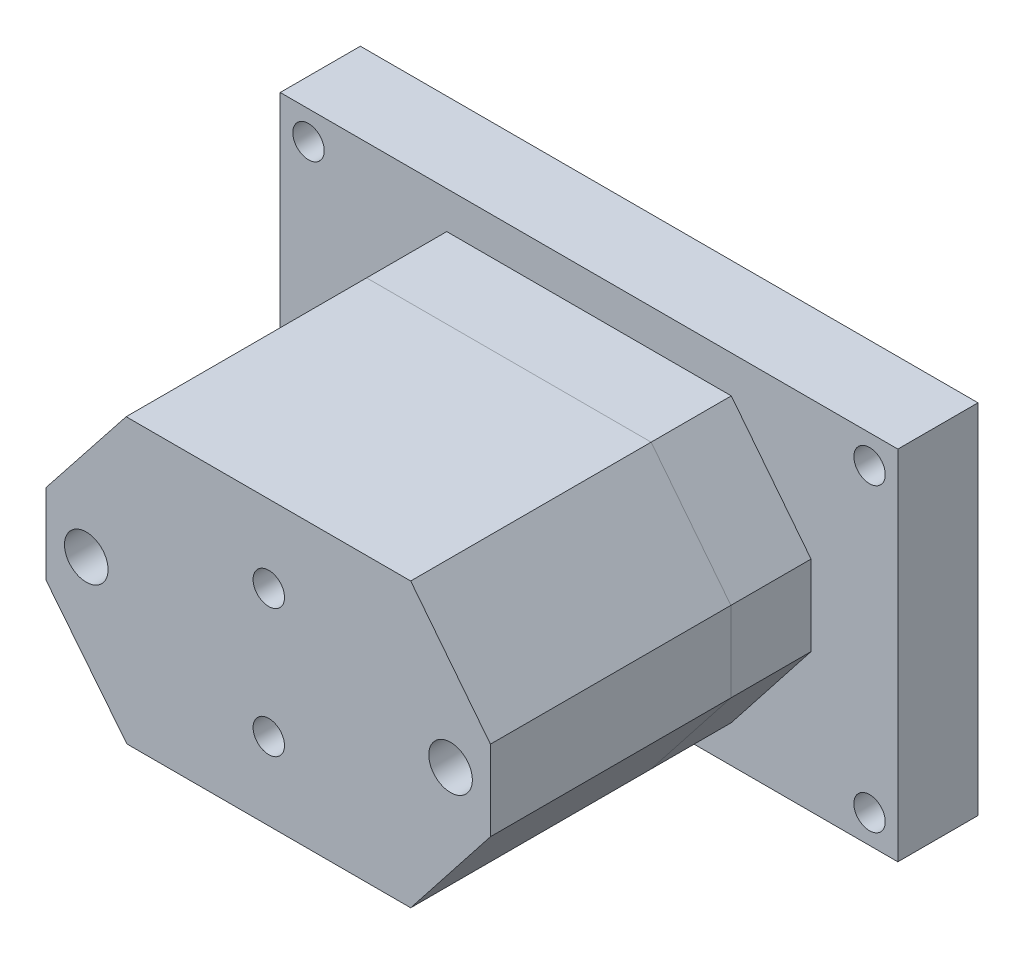
SolidWorks part; units mm, degrees
ref_plane "Alzado" through (0, 0, 0) normal (0, 0, 1) x (1, 0, 0)
ref_plane "Planta" through (0, 0, 0) normal (0, 1, 0) x (1, 0, 0)
ref_plane "Vista lateral" through (0, 0, 0) normal (1, 0, 0) x (0, 0, -1)
other "Gráfico1"
other "Gráfico (Cerrada) -1"
sketch "Croquis1" plane through (0, 0, 0) normal (0, 0, 1) x (1, 0, 0)
  line L0 (4.779, 6.731) -> (11.1125, 6.731)
  line L1 (-19.25, 19.25) -> (19.25, 19.25)
  line L2 (-19.25, 19.25) -> (-19.25, -19.25)
  line L3 (-19.25, -19.25) -> (19.25, -19.25)
  line L4 (19.25, 19.25) -> (19.25, -19.25)
  line L5 (-11.1125, 6.731) -> (-4.779, 6.731)
  line L6 (-11.1125, 6.731) -> (-11.1125, -6.731)
  line L7 (-11.1125, -6.731) -> (-4.779, -6.731)
  line L8 (11.1125, 6.731) -> (11.1125, -6.731)
  line L9 (4.779, -6.731) -> (11.1125, -6.731)
  line L10 (-8.6716, 0) -> (7.9627, 0) construction
  arc A0 (-4.779, -6.731) -> (4.779, -6.731) centre (0, 0) ccw
  arc A1 (4.779, 6.731) -> (-4.779, 6.731) centre (0, 0) ccw
  circle A2 centre (-14, 14) radius 1.632
  circle A4 centre (14, 14) radius 1.632
  circle A5 centre (14, -14) radius 1.632
  circle A6 centre (-14, -14) radius 1.632
  dimension "D1" = 3.2639
extrude "Saliente-Extruir1" add sketch "Croquis1" along normal blind 3.175
sketch "Croquis3" plane through (0, -19.25, 0) normal (0, -1, 0) x (1, 0, 0)
  line L1 (-22.5425, 18.415) -> (22.5425, 18.415)
  line L2 (-22.5425, 18.415) -> (-22.5425, 0)
  line L3 (-22.5425, 0) -> (22.5425, 0)
  line L4 (22.5425, 18.415) -> (22.5425, 0)
extrude "Saliente-Extruir3" add sketch "Croquis3" along normal blind 3.175
sketch "Croquis4" plane through (-19.25, 0, 0) normal (-1, 0, 0) x (0, 0, 1)
  line L1 (0, 19.25) -> (18.415, 19.25)
  line L2 (0, 19.25) -> (0, -19.25)
  line L3 (0, -19.25) -> (18.415, -19.25)
  line L4 (18.415, 19.25) -> (18.415, -19.25)
extrude "Saliente-Extruir4" add sketch "Croquis4" along normal blind 3.175
sketch "Croquis5" plane through (19.25, 0, 0) normal (1, 0, 0) x (0, 0, -1)
  line L0 (-12.6177, -7.6849) -> (-18.415, -7.6849)
  line L1 (0, 19.25) -> (-18.415, 19.25)
  line L2 (0, 19.25) -> (0, -19.25)
  line L3 (0, -19.25) -> (-18.415, -19.25)
  line L4 (-18.415, 19.25) -> (-18.415, -7.6849)
  line L5 (-12.3487, -12.3047) -> (-18.415, -12.3047)
  line L6 (-18.415, -12.3047) -> (-18.415, -19.25)
  arc A0 (-12.6177, -7.6849) -> (-12.3487, -12.3047) centre (-12.8905, -10.0186) cw
extrude "Saliente-Extruir5" add sketch "Croquis5" along normal blind 3.175
sketch "Croquis6" plane through (0, 19.25, 0) normal (0, 1, 0) x (1, 0, 0)
  line L1 (-22.5425, 0) -> (22.5425, 0)
  line L2 (-22.5425, 0) -> (-22.5425, -18.415)
  line L3 (-22.5425, -18.415) -> (22.5425, -18.415)
  line L4 (22.5425, 0) -> (22.5425, -18.415)
extrude "Saliente-Extruir6" add sketch "Croquis6" along normal blind 3.175
sketch "Croquis7" plane through (0, 0, 0) normal (0, 0, 1) x (1, 0, 0)
  line L0 (-22.425, -19.25) -> (-22.425, 19.25) construction
  line L1 (-35.2425, 6.35) -> (-22.425, 6.35)
  line L2 (-35.2425, 6.35) -> (-35.2425, -6.35)
  line L3 (-35.2425, -6.35) -> (-22.425, -6.35)
  line L4 (-22.425, 6.35) -> (-22.425, -6.35)
  line L6 (0, 0) -> (0, -15.2959) construction
  line L7 (22.425, 6.35) -> (22.425, -6.35)
  line L8 (35.2425, -6.35) -> (22.425, -6.35)
  line L9 (35.2425, 6.35) -> (35.2425, -6.35)
  line L10 (35.2425, 6.35) -> (22.425, 6.35)
  line L11 (-28.8338, 6.35) -> (-28.8338, -6.35) construction
  circle A1 centre (-28.8338, 0) radius 2.4892
  circle A2 centre (28.8338, 0) radius 2.4892
  dimension "D1" = 4.9784
  dimension "D2" = 12.7
extrude "Saliente-Extruir7" add sketch "Croquis7" along normal up to vertex (18.415 mm away)
sketch "Croquis10" plane through (0, 0, 0) normal (1, 0, 0) x (0, 0, -1)
  line L0 (0, -22.425) -> (-18.415, -22.425) construction
  line L1 (2.54, 22.425) -> (40.64, 22.425)
  line L2 (2.54, 22.425) -> (2.54, -22.425)
  line L3 (2.54, -22.425) -> (40.64, -22.425)
  line L4 (40.64, 22.425) -> (40.64, -22.425)
  line L5 (-18.415, 22.425) -> (0, 22.425) construction
  line L6 (0, -19.25) -> (0, -6.35) construction
  dimension "D1" = 38.1
  dimension "D2" = 2.54
extrude "Saliente-Extruir8" add sketch "Croquis10" along normal blind 35.179 and the other way up to surface (35.2425 mm away) separate body other way up to face at (-35.2425, 0, 9.2075)
sketch "Croquis11" plane through (0, 0, -2.54) normal (0, 0, 1) x (1, 0, 0)
  line L0 (22.5425, 22.425) -> (22.5425, 6.35)
  line L1 (22.5425, 6.35) -> (35.2425, 6.35)
  line L2 (35.2425, -6.35) -> (22.5425, -6.35)
  line L3 (22.5425, -6.35) -> (22.5425, -22.425)
  line L4 (-22.5425, 22.425) -> (-22.5425, 6.35)
  line L5 (-22.5425, 6.35) -> (-35.2425, 6.35)
  line L6 (-35.2425, -22.425) -> (-35.2425, 22.425) construction
  line L7 (-22.425, 6.35) -> (-35.2425, 6.35) construction
  line L8 (-35.2425, -6.35) -> (-22.425, -6.35)
  line L9 (-22.425, -6.35) -> (-22.425, -22.425)
  line L10 (-35.2425, -22.425) -> (35.179, -22.425) construction
  line L19 (-35.2425, -6.35) -> (-22.425, -22.425)
  line L20 (-35.2425, 6.35) -> (-22.5425, 22.425)
  line L21 (22.5425, 22.425) -> (35.2425, 6.35)
  line L22 (35.2425, -6.35) -> (22.5425, -22.425)
extrude "Cortar-Extruir1" cut sketch "Croquis11" against normal through all
sketch "Croquis12" plane through (0, 22.425, 0) normal (0, 1, 0) x (1, 0, 0)
  line L0 (0, 40.64) -> (0, 2.54) construction
  line L1 (-22.5425, 40.64) -> (22.5425, 40.64) construction
  line L2 (-22.5425, 2.54) -> (22.5425, 2.54) construction
  line L3 (-22.5425, 21.59) -> (22.5425, 21.59) construction
  line L4 (-22.5425, 40.64) -> (-22.5425, 2.54) construction
  line L5 (22.5425, 40.64) -> (22.5425, 2.54) construction
  circle A0 centre (0, 21.59) radius 12.7381
  dimension "D1" = 25.4762
extrude "Cortar-Extruir2" cut sketch "Croquis12" against normal through all
sketch "Croquis13" plane through (0, 0, -40.64) normal (0, 0, -1) x (-1, 0, 0)
  line L0 (-35.179, 0) -> (35.2425, 0) construction
  line L1 (35.2425, 6.35) -> (35.2425, -6.35) construction
  line L2 (-28.8607, 6.35) -> (-28.8607, -6.35) construction
  line L3 (-22.5425, 6.35) -> (-35.179, 6.35) construction
  line L4 (-35.179, -6.35) -> (-22.5425, -6.35) construction
  line L5 (-35.179, -6.35) -> (-35.179, 6.35) construction
  circle A0 centre (-28.8607, 0) radius 3.45
  dimension "D1" = 6.9
extrude "Cortar-Extruir3" cut sketch "Croquis13" against normal through all and the other way through all
mirror "Simetría1" about plane through (0, 0, 0) normal (1, 0, 0) of "Cortar-Extruir3"
sketch "Croquis14" plane through (0, 22.425, 0) normal (0, 1, 0) x (1, 0, 0)
  circle A0 centre (0, 21.59) radius 12.7381
  circle A1 centre (0, 21.59) radius 12.7381 construction
extrude "Saliente-Extruir9" add sketch "Croquis14" against normal blind 3.175
sketch "Croquis15" plane through (0, 0, -2.54) normal (0, 0, 1) x (1, 0, 0)
  line L0 (0.0587, 22.425) -> (0.0587, -22.425) construction
  line L2 (-22.425, -22.425) -> (22.5425, -22.425) construction
  line L3 (-19.8313, 0) -> (20.5848, 0) construction
  circle A2 centre (0.0587, 10.1598) radius 2.4892
  circle A3 centre (0.0587, -10.1598) radius 2.4892
  dimension "D1" = 4.9784
  dimension "D2" = 10.16
extrude "Cortar-Extruir4" cut sketch "Croquis15" against normal through all
sketch "Croquis17" plane through (0, 0, -2.54) normal (0, 0, 1) x (1, 0, 0)
  line L0 (-35.2425, 6.35) -> (-22.5425, 22.425)
  line L1 (-22.5425, 22.425) -> (-22.5425, 6.35)
  line L2 (-22.5425, 6.35) -> (-35.2425, 6.35)
  line L3 (-35.2425, -6.35) -> (-22.425, -6.35)
  line L4 (-22.425, -6.35) -> (-22.425, -22.425)
  line L5 (-22.425, -22.425) -> (-35.2425, -6.35)
  line L6 (22.5425, 22.425) -> (35.179, 6.35)
  line L7 (35.179, 6.35) -> (22.5425, 6.35)
  line L8 (22.5425, 6.35) -> (22.5425, 22.425)
  line L9 (35.179, -6.35) -> (22.5425, -6.35)
  line L10 (22.5425, -6.35) -> (22.5425, -22.425)
  line L11 (22.5425, -22.425) -> (35.179, -6.35)
  line M5 (22.5425, -22.425) -> (22.5425, -6.35)
  line M6 (22.5425, -6.35) -> (35.179, -6.35)
  line M8 (35.179, 6.35) -> (22.5425, 6.35)
  line M9 (22.5425, 6.35) -> (22.5425, 22.425)
  line M11 (-22.5425, 22.425) -> (-22.5425, 6.35)
  line M12 (-22.5425, 6.35) -> (-35.2425, 6.35)
  line M14 (-35.2425, -6.35) -> (-22.425, -6.35)
  line M15 (-22.425, -6.35) -> (-22.425, -22.425)
extrude "Saliente-Extruir10" add sketch "Croquis17" against normal up to surface (38.1 mm away) contours L0 M12 M11 | L5 M15 M14 | L11 M5 M6 | L6 M9 M8 up to face at (2.5479, 10.1598, -40.64)
delete or keep bodies "Sólido-Eliminar/Conservar 1" type keep bodies bodies 121
sketch "Croquis18" plane through (0, 0, -40.64) normal (0, 0, -1) x (-1, 0, 0)
  line L0 (-22.5425, 22.425) -> (22.5425, 22.425)
  line L1 (22.5425, 22.425) -> (35.2425, 6.35)
  line L2 (35.2425, 6.35) -> (35.2425, -6.35)
  line L3 (35.2425, -6.35) -> (22.425, -22.425)
  line L4 (22.425, -22.425) -> (-22.5425, -22.425)
  line L5 (-22.5425, -22.425) -> (-35.179, -6.35)
  line L6 (-35.179, -6.35) -> (-35.179, 6.35)
  line L7 (-35.179, 6.35) -> (-22.5425, 22.425)
extrude "Saliente-Extruir11" add sketch "Croquis18" along normal blind 12.7 separate body
delete or keep bodies "Sólido-Eliminar/Conservar 3" [suppressed] type keep bodies bodies 123
sketch "Croquis19" plane through (0, 0, -53.34) normal (0, 0, -1) x (-1, 0, 0)
  line L0 (0, -23.8125) -> (0, 23.8125) construction
  line L1 (-48.9331, -28.321) -> (48.9331, -28.321)
  line L2 (-48.9331, -28.321) -> (-48.9331, 28.321)
  line L3 (-48.9331, 28.321) -> (48.9331, 28.321)
  line L4 (48.9331, -28.321) -> (48.9331, 28.321)
  line L5 (-48.9331, -28.321) -> (48.9331, 28.321) construction
  line L6 (-48.9331, 28.321) -> (48.9331, -28.321) construction
  line L7 (-44.45, -23.8125) -> (44.45, -23.8125) construction
  line L8 (-44.45, -23.8125) -> (-44.45, 23.8125) construction
  line L9 (-44.45, 23.8125) -> (44.45, 23.8125) construction
  line L10 (44.45, -23.8125) -> (44.45, 23.8125) construction
  line L11 (-44.45, -23.8125) -> (44.45, 23.8125) construction
  line L12 (-44.45, 23.8125) -> (44.45, -23.8125) construction
  circle A0 centre (-44.45, 23.8125) radius 2.4892
  circle A1 centre (-44.45, -23.8125) radius 2.4892
  circle A2 centre (44.45, -23.8125) radius 2.4892
  circle A3 centre (44.45, 23.8125) radius 2.4892
  point P0 (0, 0)
  point P6 (0, 0)
  dimension "D5" = 4.9784
  dimension "D6" = 4.9784
  dimension "D1" = 97.8662
  dimension "D2" = 56.642
  dimension "D3" = 47.625
  dimension "D4" = 88.9
extrude "Saliente-Extruir12" add sketch "Croquis19" along normal blind 12.7
sketch "Croquis20" plane through (0, 0, -2.54) normal (0, 0, 1) x (1, 0, 0)
  circle A3 centre (28.8607, 0) radius 3.45 construction
  circle A4 centre (0.0587, -10.1598) radius 2.4892 construction
  circle A5 centre (-28.8607, 0) radius 3.45 construction
  circle A6 centre (0.0587, 10.1598) radius 2.4892 construction
  circle A7 centre (28.8607, 0) radius 3.45
  circle A8 centre (0.0587, -10.1598) radius 2.4892
  circle A9 centre (-28.8607, 0) radius 3.45
  circle A10 centre (0.0587, 10.1598) radius 2.4892
extrude "Cortar-Extruir5" cut sketch "Croquis20" against normal through all
